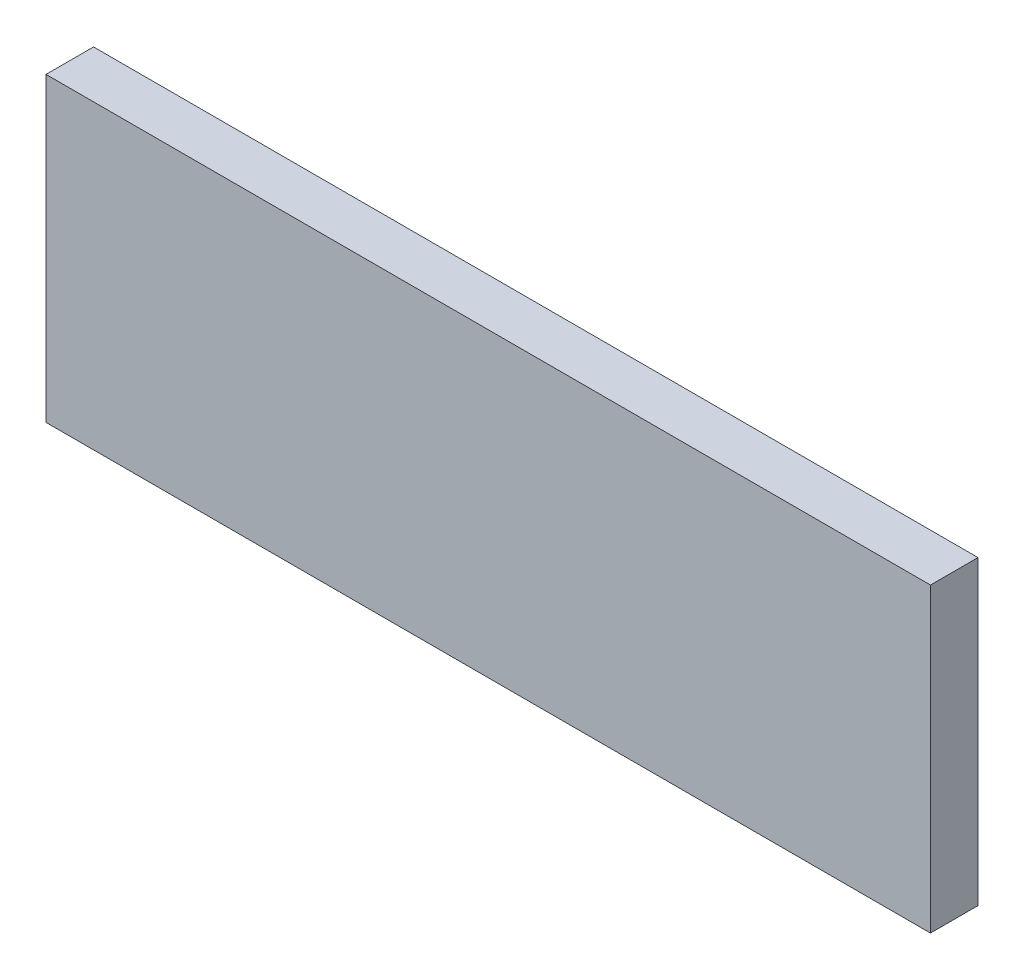
SolidWorks part; units mm, degrees
ref_plane "Plano frontal" through (0, 0, 0) normal (0, 0, 1) x (1, 0, 0)
ref_plane "Plano superior" through (0, 0, 0) normal (0, 1, 0) x (1, 0, 0)
ref_plane "Plano direito" through (0, 0, 0) normal (1, 0, 0) x (0, 0, -1)
sketch "Esboço56" plane through (55.1891, 0, 0) normal (-1, 0, 0) x (0, 0, 1)
  line L0 (5, -3.6695) -> (38, -3.6695) construction
  line L1 (39.32, -3.6695) -> (34.32, -3.6695)
  line L2 (39.32, -3.6695) -> (39.32, -35.3645)
  line L3 (39.32, -35.3645) -> (34.32, -35.3645)
  line L4 (34.32, -3.6695) -> (34.32, -35.3645)
  line L5 (38, -35.3645) -> (5, -35.3645) construction
  arc A0 (17.5, -49.5145) -> (17.5, 10.4855) centre (17.5, -19.5145) ccw construction
  point P11 (47.5, -19.5145)
  dimension "D1" = 8.18
extrude "Ressalto-extrusão13" add sketch "Esboço56" along normal blind 93
